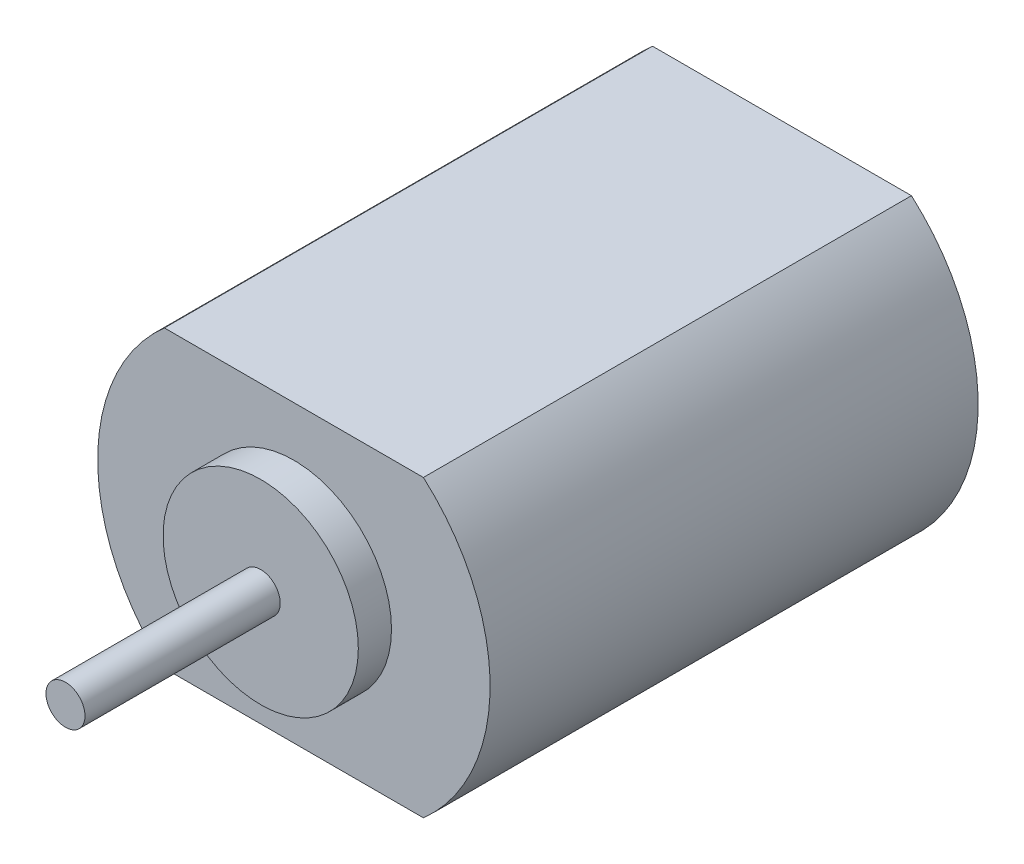
SolidWorks part; units mm, degrees
ref_plane "Front Plane" through (0, 0, 0) normal (0, 0, 1) x (1, 0, 0)
ref_plane "Top Plane" through (0, 0, 0) normal (0, 1, 0) x (1, 0, 0)
ref_plane "Right Plane" through (0, 0, 0) normal (1, 0, 0) x (0, 0, -1)
sketch "Sketch1" plane through (0, 0, 0) normal (0, 0, 1) x (1, 0, 0)
  line L1 (-6.6332, -7.55) -> (6.6332, -7.55)
  line L3 (-6.6332, 7.55) -> (6.6332, 7.55)
  line L5 (-9.3147, -3.7734) -> (9.3147, 3.7734) construction
  line L6 (-9.3147, 3.7734) -> (9.3147, -3.7734) construction
  arc A0 (-6.6332, 7.55) -> (-6.6332, -7.55) centre (0, 0) ccw
  arc A1 (6.6332, -7.55) -> (6.6332, 7.55) centre (0, 0) ccw
extrude "Boss-Extrude1" add sketch "Sketch1" along normal blind 25
sketch "Sketch2" plane through (0, 0, 25) normal (0, 0, 1) x (1, 0, 0)
  circle A0 centre (0, 0) radius 5
extrude "Boss-Extrude2" add sketch "Sketch2" along normal blind 1.7
sketch "Sketch3" plane through (0, 0, 26.7) normal (0, 0, 1) x (1, 0, 0)
  circle A1 centre (0, 0) radius 1
extrude "Boss-Extrude3" add sketch "Sketch3" along normal blind 10
